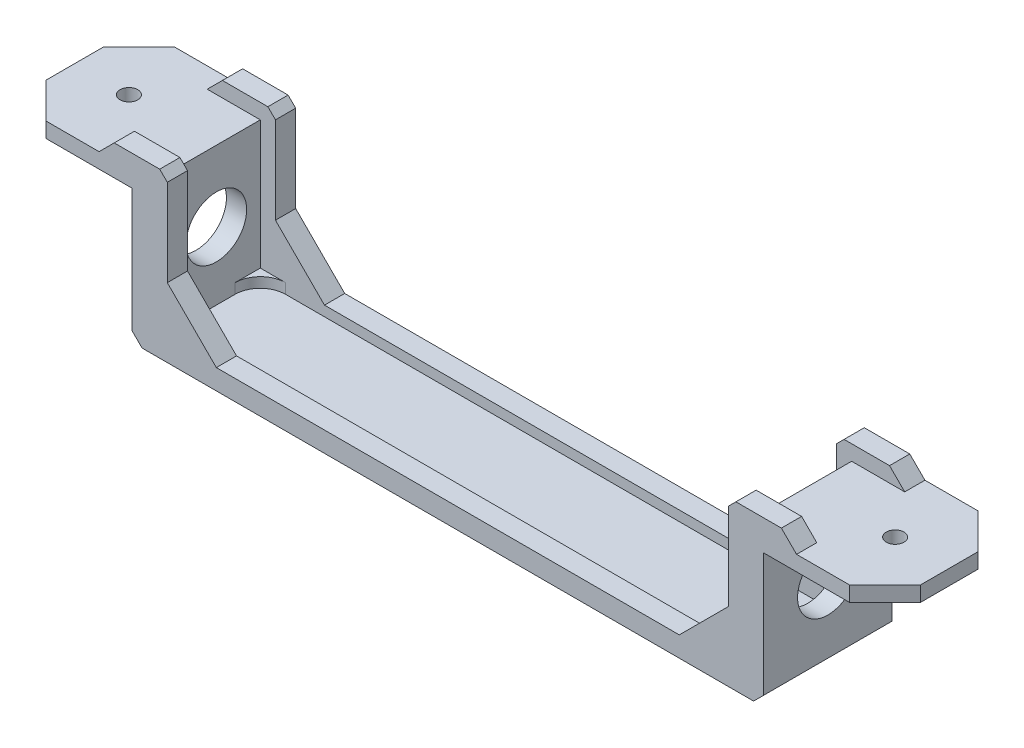
SolidWorks part; units mm, degrees
ref_plane "Front Plane" through (0, 0, 0) normal (0, 0, 1) x (1, 0, 0)
ref_plane "Top Plane" through (0, 0, 0) normal (0, 1, 0) x (1, 0, 0)
ref_plane "Right Plane" through (0, 0, 0) normal (1, 0, 0) x (0, 0, -1)
sketch "Sketch1" plane through (0, 0, 0) normal (0, 1, 0) x (1, 0, 0)
  line L1 (-62.5, 12.7) -> (62.5, 12.7)
  line L2 (-62.5, 12.7) -> (-62.5, -12.7)
  line L3 (-62.5, -12.7) -> (62.5, -12.7)
  line L4 (62.5, 12.7) -> (62.5, -12.7)
  line L5 (-62.5, 12.7) -> (62.5, -12.7) construction
  line L6 (-62.5, -12.7) -> (62.5, 12.7) construction
  point P0 (0, 0)
  dimension "D1" = 25.4
  dimension "D2" = 125
extrude "Boss-Extrude1" add sketch "Sketch1" along normal blind 4
sketch "Sketch2" plane through (0, 4, 0) normal (0, 1, 0) x (1, 0, 0)
  line L0 (62.5, 12.7) -> (-62.5, 12.7) construction
  line L1 (-58.5, 8.7) -> (58.5, 8.7)
  line L2 (-58.5, 8.7) -> (-58.5, -8.7)
  line L3 (-58.5, -8.7) -> (58.5, -8.7)
  line L4 (58.5, 8.7) -> (58.5, -8.7)
  line L5 (-58.5, 8.7) -> (58.5, -8.7) construction
  line L6 (-58.5, -8.7) -> (58.5, 8.7) construction
  line L7 (-62.5, 12.7) -> (-62.5, -12.7) construction
  point P0 (0, 0)
  dimension "D1" = 4
  dimension "D2" = 4
extrude "Cut-Extrude1" cut sketch "Sketch2" against normal blind 2
fillet "Fillet1" radius 5 4 edges at (58.5, 3, 8.7) (58.5, 3, -8.7) (-58.5, 3, 8.7) (-58.5, 3, -8.7)
sketch "Sketch3" plane through (0, 4, 0) normal (0, 1, 0) x (1, 0, 0)
  line L0 (-62.5, -12.7) -> (62.5, -12.7) construction
  line L1 (62.5, 12.7) -> (58.5, 12.7)
  line L2 (62.5, 12.7) -> (62.5, -12.7)
  line L3 (62.5, -12.7) -> (58.5, -12.7)
  line L4 (58.5, 12.7) -> (58.5, -12.7)
  line L6 (-62.5, 12.7) -> (-58.5, 12.7)
  line L7 (-62.5, 12.7) -> (-62.5, -12.7)
  line L8 (-62.5, -12.7) -> (-58.5, -12.7)
  line L9 (-58.5, 12.7) -> (-58.5, -12.7)
extrude "Boss-Extrude2" add sketch "Sketch3" along normal blind 25.4
chamfer "Chamfer1" distance 2 angle 45 2 edges at (-62.5, 0, 0) (62.5, 0, 0)
sketch "Sketch4" plane through (62.5, 0, 0) normal (1, 0, 0) x (0, 0, -1)
  line L1 (-12.7, 29.4) -> (12.7, 29.4) construction
  circle A0 centre (0, 15.4) radius 6
  dimension "D1" = 14
  dimension "D2" = 12
extrude "Cut-Extrude3" cut sketch "Sketch4" against normal blind 135.4
sketch "Sketch5" plane through (-62.5, 0, 0) normal (-1, 0, 0) x (0, 0, 1)
  line L0 (12.7, 29.4) -> (12.7, 2) construction
  line L1 (-12.7, 29.4) -> (12.7, 29.4)
  line L2 (-12.7, 29.4) -> (-12.7, 26.4)
  line L3 (-12.7, 26.4) -> (12.7, 26.4)
  line L4 (12.7, 29.4) -> (12.7, 26.4)
  dimension "D1" = 3
extrude "Boss-Extrude3" add sketch "Sketch5" along normal blind 24
sketch "Sketch6" plane through (62.5, 0, 0) normal (1, 0, 0) x (0, 0, -1)
  line L0 (12.7, 29.4) -> (12.7, 2) construction
  line L1 (-12.7, 29.4) -> (12.7, 29.4)
  line L2 (-12.7, 29.4) -> (-12.7, 26.4)
  line L3 (-12.7, 26.4) -> (12.7, 26.4)
  line L4 (12.7, 29.4) -> (12.7, 26.4)
  dimension "D1" = 3
extrude "Boss-Extrude4" add sketch "Sketch6" along normal blind 24
sketch "Sketch7" plane through (0, 0, 12.7) normal (0, 0, 1) x (1, 0, 0)
  line L0 (-58.5, 16.7) -> (-45.8, 4)
  line L1 (-58.5, 29.4) -> (-58.5, 4) construction
  line L2 (-58.5, 4) -> (58.5, 4) construction
  line L3 (-45.8, 4) -> (-58.5, 4)
  line L4 (-58.5, 4) -> (-58.5, 16.7)
  line L5 (58.5, 16.7) -> (45.8, 4)
  line L6 (58.5, 29.4) -> (58.5, 4) construction
  line L7 (45.8, 4) -> (58.5, 4)
  line L8 (58.5, 4) -> (58.5, 16.7)
extrude "Boss-Extrude5" add sketch "Sketch7" against normal blind 4
sketch "Sketch8" plane through (0, 0, -12.7) normal (0, 0, -1) x (-1, 0, 0)
  line L0 (-58.5, 16.7) -> (-45.8, 4)
  line L1 (-58.5, 29.4) -> (-58.5, 4) construction
  line L2 (-58.5, 4) -> (58.5, 4) construction
  line L3 (-45.8, 4) -> (-58.5, 4)
  line L4 (-58.5, 4) -> (-58.5, 16.7)
  line L5 (58.5, 16.7) -> (45.8, 4)
  line L6 (58.5, 29.4) -> (58.5, 4) construction
  line L7 (45.8, 4) -> (58.5, 4)
  line L8 (58.5, 4) -> (58.5, 16.7)
extrude "Boss-Extrude6" add sketch "Sketch8" against normal blind 4
sketch "Sketch9" plane through (0, 29.4, 0) normal (0, 1, 0) x (1, 0, 0)
  line L0 (86.5, 12.7) -> (86.5, -12.7) construction
  circle A0 centre (75.8, 0) radius 1.75
  circle A1 centre (-75.8, 0) radius 1.75
  dimension "D1" = 3.5
  dimension "D2" = 3.5
  dimension "D3" = 151.6
  dimension "D4" = 10.7
extrude "Cut-Extrude4" cut sketch "Sketch9" against normal blind 4
chamfer "Chamfer2" distance 7 angle 45 4 edges at (86.5, 27.9, 12.7) (86.5, 27.9, -12.7) (-86.5, 27.9, 12.7) (-86.5, 27.9, -12.7)
sketch "Sketch10" plane through (0, 0, -12.7) normal (0, 0, -1) x (-1, 0, 0)
  line L0 (-69, 29.4) -> (-66, 32.4)
  line L1 (-79.5, 29.4) -> (-58.5, 29.4) construction
  line L2 (-66, 32.4) -> (-55.5, 32.4)
  line L3 (-55.5, 32.4) -> (-55.5, 13.7)
  line L4 (-45.8, 4) -> (-58.5, 16.7) construction
  line L5 (-55.5, 13.7) -> (-58.5, 16.7)
  line L6 (-58.5, 16.7) -> (-58.5, 29.4)
  line L7 (-58.5, 29.4) -> (-69, 29.4)
  line L8 (69, 29.4) -> (66, 32.4)
  line L9 (58.5, 29.4) -> (79.5, 29.4) construction
  line L10 (66, 32.4) -> (55.5, 32.4)
  line L11 (55.5, 32.4) -> (55.5, 13.7)
  line L12 (58.5, 16.7) -> (45.8, 4) construction
  line L13 (55.5, 13.7) -> (58.5, 16.7)
  line L14 (58.5, 16.7) -> (58.5, 29.4)
  line L15 (58.5, 29.4) -> (69, 29.4)
  dimension "D1" = 3
  dimension "D2" = 3
  dimension "D3" = 3
  dimension "D4" = 3
extrude "Boss-Extrude7" add sketch "Sketch10" against normal blind 4
sketch "Sketch11" plane through (0, 0, 12.7) normal (0, 0, 1) x (1, 0, 0)
  line L0 (69, 29.4) -> (66, 32.4)
  line L1 (58.5, 29.4) -> (79.5, 29.4) construction
  line L2 (66, 32.4) -> (55.5, 32.4)
  line L3 (55.5, 32.4) -> (55.5, 13.7)
  line L4 (55.5, 13.7) -> (58.5, 16.7)
  line L5 (58.5, 16.7) -> (58.5, 29.4)
  line L6 (58.5, 29.4) -> (69, 29.4)
  line L7 (-69, 29.4) -> (-66, 32.4)
  line L8 (-79.5, 29.4) -> (-58.5, 29.4) construction
  line L9 (-66, 32.4) -> (-55.5, 32.4)
  line L10 (-55.5, 32.4) -> (-55.5, 13.7)
  line L11 (-55.5, 13.7) -> (-58.5, 16.7)
  line L12 (-58.5, 4) -> (-58.5, 29.4) construction
  line L13 (-58.5, 16.7) -> (-58.5, 29.4)
  line L14 (-58.5, 29.4) -> (-69, 29.4)
extrude "Boss-Extrude8" add sketch "Sketch11" against normal blind 4
chamfer "Chamfer3" distance 1.5 angle 45 4 edges at (55.5, 32.4, -10.7) (55.5, 32.4, 10.7) (-55.5, 32.4, -10.7) (-55.5, 32.4, 10.7)
